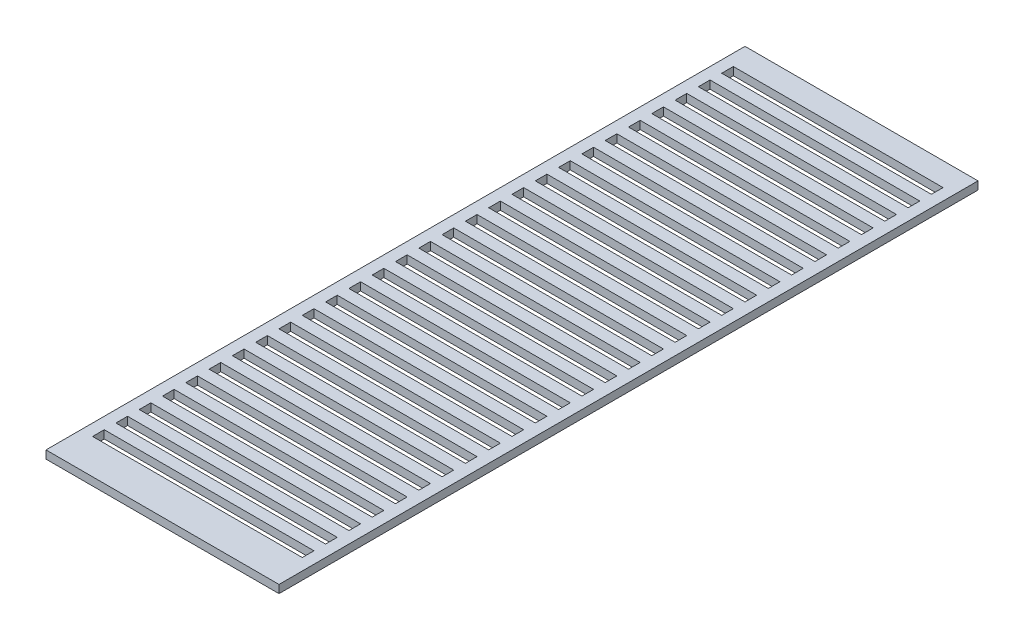
SolidWorks part; units mm, degrees
ref_plane "Front Plane" through (0, 0, 0) normal (0, 0, 1) x (1, 0, 0)
ref_plane "Top Plane" through (0, 0, 0) normal (0, 1, 0) x (1, 0, 0)
ref_plane "Right Plane" through (0, 0, 0) normal (1, 0, 0) x (0, 0, -1)
sketch "Sketch1" plane through (0, 0, 0) normal (0, 1, 0) x (1, 0, 0)
  line L0 (-57.15, 165.1) -> (-57.15, 158.75)
  line L1 (-63.5, 190.5) -> (63.5, 190.5)
  line L2 (-63.5, 190.5) -> (-63.5, -190.5)
  line L3 (-63.5, -190.5) -> (63.5, -190.5)
  line L4 (63.5, 190.5) -> (63.5, -190.5)
  line L7 (-57.15, 177.8) -> (57.15, 177.8)
  line L8 (-63.5, 0) -> (0, 0) construction
  line L9 (-57.15, 177.8) -> (-57.15, 171.45)
  line L10 (-57.15, 171.45) -> (57.15, 171.45)
  line L11 (57.15, 177.8) -> (57.15, 171.45)
  line L12 (-57.15, 177.8) -> (57.15, 171.45) construction
  line L13 (-57.15, 171.45) -> (57.15, 177.8) construction
  line L14 (-57.15, 165.1) -> (57.15, 165.1)
  line L15 (57.15, 165.1) -> (57.15, 158.75)
  line L16 (-57.15, 158.75) -> (57.15, 158.75)
  line L17 (-57.15, 152.4) -> (-57.15, 146.05)
  line L18 (-57.15, 152.4) -> (57.15, 152.4)
  line L19 (57.15, 152.4) -> (57.15, 146.05)
  line L20 (-57.15, 146.05) -> (57.15, 146.05)
  line L21 (-57.15, 139.7) -> (-57.15, 133.35)
  line L22 (-57.15, 139.7) -> (57.15, 139.7)
  line L23 (57.15, 139.7) -> (57.15, 133.35)
  line L24 (-57.15, 133.35) -> (57.15, 133.35)
  line L25 (-57.15, 127) -> (-57.15, 120.65)
  line L26 (-57.15, 127) -> (57.15, 127)
  line L27 (57.15, 127) -> (57.15, 120.65)
  line L28 (-57.15, 120.65) -> (57.15, 120.65)
  line L29 (-57.15, 114.3) -> (-57.15, 107.95)
  line L30 (-57.15, 114.3) -> (57.15, 114.3)
  line L31 (57.15, 114.3) -> (57.15, 107.95)
  line L32 (-57.15, 107.95) -> (57.15, 107.95)
  line L33 (-57.15, 101.6) -> (-57.15, 95.25)
  line L34 (-57.15, 101.6) -> (57.15, 101.6)
  line L35 (57.15, 101.6) -> (57.15, 95.25)
  line L36 (-57.15, 95.25) -> (57.15, 95.25)
  line L37 (-57.15, 88.9) -> (-57.15, 82.55)
  line L38 (-57.15, 88.9) -> (57.15, 88.9)
  line L39 (57.15, 88.9) -> (57.15, 82.55)
  line L40 (-57.15, 82.55) -> (57.15, 82.55)
  line L41 (-57.15, 76.2) -> (-57.15, 69.85)
  line L42 (-57.15, 76.2) -> (57.15, 76.2)
  line L43 (57.15, 76.2) -> (57.15, 69.85)
  line L44 (-57.15, 69.85) -> (57.15, 69.85)
  line L45 (-57.15, 63.5) -> (-57.15, 57.15)
  line L46 (-57.15, 63.5) -> (57.15, 63.5)
  line L47 (57.15, 63.5) -> (57.15, 57.15)
  line L48 (-57.15, 57.15) -> (57.15, 57.15)
  line L49 (-57.15, 50.8) -> (-57.15, 44.45)
  line L50 (-57.15, 50.8) -> (57.15, 50.8)
  line L51 (57.15, 50.8) -> (57.15, 44.45)
  line L52 (-57.15, 44.45) -> (57.15, 44.45)
  line L53 (-57.15, 38.1) -> (-57.15, 31.75)
  line L54 (-57.15, 38.1) -> (57.15, 38.1)
  line L55 (57.15, 38.1) -> (57.15, 31.75)
  line L56 (-57.15, 31.75) -> (57.15, 31.75)
  line L57 (-57.15, 25.4) -> (-57.15, 19.05)
  line L58 (-57.15, 25.4) -> (57.15, 25.4)
  line L59 (57.15, 25.4) -> (57.15, 19.05)
  line L60 (-57.15, 19.05) -> (57.15, 19.05)
  line L61 (-57.15, 12.7) -> (-57.15, 6.35)
  line L62 (-57.15, 12.7) -> (57.15, 12.7)
  line L63 (57.15, 12.7) -> (57.15, 6.35)
  line L64 (-57.15, 6.35) -> (57.15, 6.35)
  line L65 (-57.15, 0) -> (-57.15, -6.35)
  line L66 (-57.15, 0) -> (57.15, 0)
  line L67 (57.15, 0) -> (57.15, -6.35)
  line L68 (-57.15, -6.35) -> (57.15, -6.35)
  line L69 (-57.15, -12.7) -> (-57.15, -19.05)
  line L70 (-57.15, -12.7) -> (57.15, -12.7)
  line L71 (57.15, -12.7) -> (57.15, -19.05)
  line L72 (-57.15, -19.05) -> (57.15, -19.05)
  line L73 (-57.15, -25.4) -> (-57.15, -31.75)
  line L74 (-57.15, -25.4) -> (57.15, -25.4)
  line L75 (57.15, -25.4) -> (57.15, -31.75)
  line L76 (-57.15, -31.75) -> (57.15, -31.75)
  line L77 (-57.15, -38.1) -> (-57.15, -44.45)
  line L78 (-57.15, -38.1) -> (57.15, -38.1)
  line L79 (57.15, -38.1) -> (57.15, -44.45)
  line L80 (-57.15, -44.45) -> (57.15, -44.45)
  line L81 (-57.15, -50.8) -> (-57.15, -57.15)
  line L82 (-57.15, -50.8) -> (57.15, -50.8)
  line L83 (57.15, -50.8) -> (57.15, -57.15)
  line L84 (-57.15, -57.15) -> (57.15, -57.15)
  line L85 (-57.15, -63.5) -> (-57.15, -69.85)
  line L86 (-57.15, -63.5) -> (57.15, -63.5)
  line L87 (57.15, -63.5) -> (57.15, -69.85)
  line L88 (-57.15, -69.85) -> (57.15, -69.85)
  line L89 (-57.15, -76.2) -> (-57.15, -82.55)
  line L90 (-57.15, -76.2) -> (57.15, -76.2)
  line L91 (57.15, -76.2) -> (57.15, -82.55)
  line L92 (-57.15, -82.55) -> (57.15, -82.55)
  line L93 (-57.15, -88.9) -> (-57.15, -95.25)
  line L94 (-57.15, -88.9) -> (57.15, -88.9)
  line L95 (57.15, -88.9) -> (57.15, -95.25)
  line L96 (-57.15, -95.25) -> (57.15, -95.25)
  line L97 (-57.15, -101.6) -> (-57.15, -107.95)
  line L98 (-57.15, -101.6) -> (57.15, -101.6)
  line L99 (57.15, -101.6) -> (57.15, -107.95)
  line L100 (-57.15, -107.95) -> (57.15, -107.95)
  line L101 (-57.15, -114.3) -> (-57.15, -120.65)
  line L102 (-57.15, -114.3) -> (57.15, -114.3)
  line L103 (57.15, -114.3) -> (57.15, -120.65)
  line L104 (-57.15, -120.65) -> (57.15, -120.65)
  line L105 (-57.15, -127) -> (-57.15, -133.35)
  line L106 (-57.15, -127) -> (57.15, -127)
  line L107 (57.15, -127) -> (57.15, -133.35)
  line L108 (-57.15, -133.35) -> (57.15, -133.35)
  line L109 (-57.15, -139.7) -> (-57.15, -146.05)
  line L110 (-57.15, -139.7) -> (57.15, -139.7)
  line L111 (57.15, -139.7) -> (57.15, -146.05)
  line L112 (-57.15, -146.05) -> (57.15, -146.05)
  line L113 (-57.15, -152.4) -> (-57.15, -158.75)
  line L114 (-57.15, -152.4) -> (57.15, -152.4)
  line L115 (57.15, -152.4) -> (57.15, -158.75)
  line L116 (-57.15, -158.75) -> (57.15, -158.75)
  line L117 (-57.15, -165.1) -> (-57.15, -171.45)
  line L118 (-57.15, -165.1) -> (57.15, -165.1)
  line L119 (57.15, -165.1) -> (57.15, -171.45)
  line L120 (-57.15, -171.45) -> (57.15, -171.45)
  point P0 (0, 0)
  point P7 (0, 174.625)
  point P11 (0, -190.5)
  point P12 (-63.5, 0)
  point P34 (0, 0)
  point P169 (0, 0)
  dimension "D3" = 12.7
  dimension "D4" = 6.35
  dimension "D7" = 6.35
  dimension "D1" = 127
  dimension "D2" = 381
  dimension "D5" = 6.35
  dimension "D6" = 28
extrude "Boss-Extrude1" add sketch "Sketch1" along normal blind 4.3656
